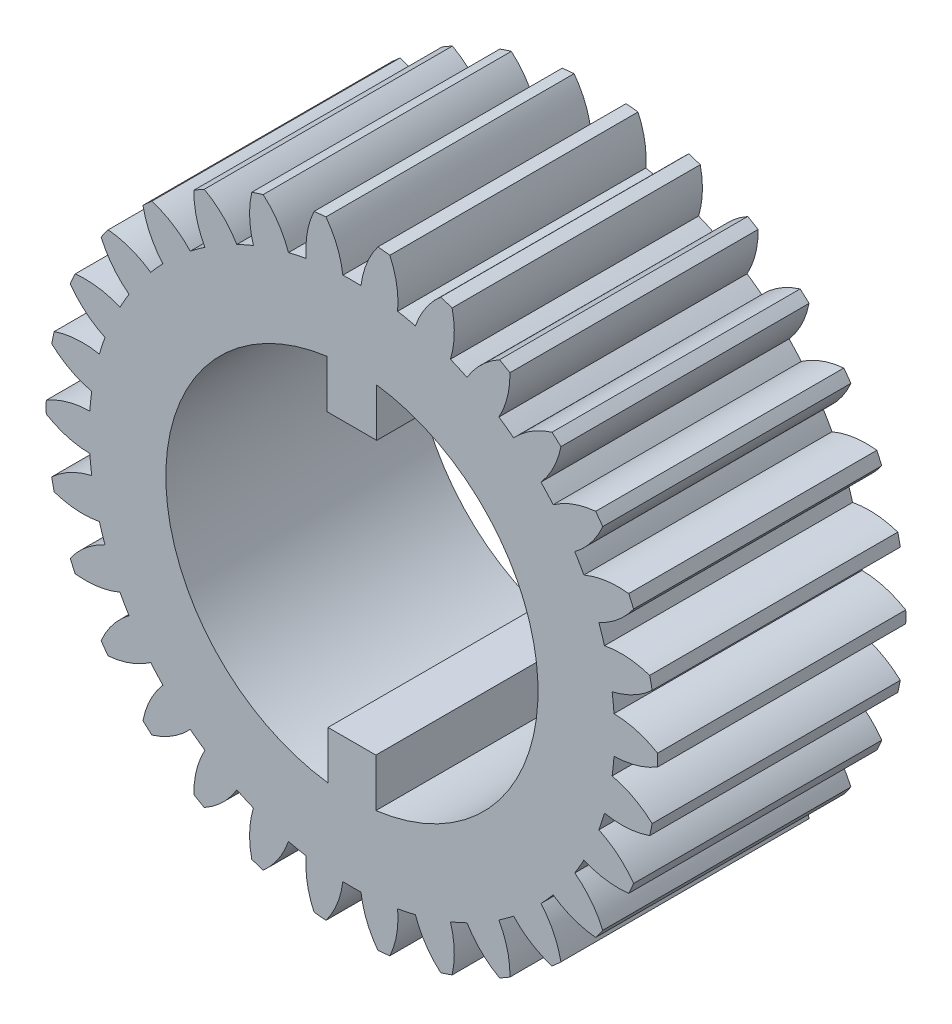
SolidWorks part; units mm, degrees
ref_plane "Front" through (0, 0, 0) normal (0, 0, 1) x (1, 0, 0)
ref_plane "Top" through (0, 0, 0) normal (0, 1, 0) x (1, 0, 0)
ref_plane "Right" through (0, 0, 0) normal (1, 0, 0) x (0, 0, -1)
sketch "Эскиз1" plane through (0, 0, 0) normal (0, 0, 1) x (1, 0, 0)
  circle A0 centre (0, 0) radius 10.5875 construction
  circle A1 centre (0, 0) radius 11.5 construction
  circle A2 centre (0, 0) radius 12.32
  circle A3 centre (0, 0) radius 10.805 construction
  dimension "D1" = 21.175
  dimension "D2" = 23
  dimension "D3" = 24.64
  dimension "D4" = 21.61
extrude "Бобышка-Вытянуть1" add sketch "Эскиз1" along normal mid plane 10
sketch "Эскиз2" plane through (0, 0, 5) normal (0, 0, 1) x (1, 0, 0)
  line L0 (-0.9448, 15.1928) -> (0, 0) construction
  line L1 (-0.7321, 11.7723) -> (-4.9391, 9.6101) construction
  line L2 (-0.6, 11.4843) -> (0.6, 11.4843) construction
  line L3 (0, 0) -> (0, 12.32) construction
  circle A0 centre (0, 0) radius 12.32 construction
  circle A1 centre (0, 0) radius 10.805 construction
  arc A2 (-1.4587, 12.7367) -> (-0.3658, 10.5812) centre (-3.8896, 10.1495) cw
  circle A3 centre (0, 0) radius 10.5875 construction
  circle A4 centre (0, 0) radius 11.5 construction
  arc A5 (1.4587, 12.7367) -> (0.3658, 10.5812) centre (3.8896, 10.1495) ccw
  arc A6 (-0.3658, 10.5812) -> (0.3658, 10.5812) centre (0, 0) cw
  circle A8 centre (0, 0) radius 12.82
  arc A9 (1.4587, 12.7367) -> (-1.4587, 12.7367) centre (0, 0) ccw
  point P3 (-0.7321, 11.7723)
  dimension "D1" = 0.525
  dimension "D2" = 1.2
  dimension "D3" = 4.7301
  dimension "D4" = 1.18
  dimension "D5" = 0.5
sketch "Эскиз4" plane through (0, 0, 0) normal (0, 1, 0) x (1, 0, 0)
  line L0 (0, 5) -> (0, -5)
  line L1 (12.32, 5) -> (-12.32, 5) construction
  line L3 (-12.32, -5) -> (12.32, -5) construction
  line L4 (0, -50) -> (0, 50) construction
  dimension "D1" = 0
curve "Кривая1"
sketch "Эскиз5" plane through (0, 0, -5) normal (0, 0, 1) x (1, 0, 0)
  line L0 (-0.9448, 15.1928) -> (0, 0) construction
  line L1 (-0.7321, 11.7723) -> (-4.9391, 9.6101) construction
  line L2 (-0.6, 11.4843) -> (0.6, 11.4843) construction
  line L3 (0, 0) -> (0, 12.32) construction
  arc A2 (-1.4587, 12.7367) -> (-0.3658, 10.5812) centre (-3.8896, 10.1495) cw
  arc A5 (1.4587, 12.7367) -> (0.3658, 10.5812) centre (3.8896, 10.1495) ccw
  arc A6 (-0.3658, 10.5812) -> (0.3658, 10.5812) centre (0, 0) cw
  arc A9 (1.4587, 12.7367) -> (-1.4587, 12.7367) centre (0, 0) ccw
  point P3 (-0.7321, 11.7723)
loft "Вырез-По сечениям1" cut profiles "Эскиз5", "Эскиз2"
pattern_circular "Круговой массив1" count 30 over 360 about axis through (0, 0, 0) along (0, 0, 1) of "Вырез-По сечениям1"
sketch "Эскиз6" plane through (0, 0, 5) normal (0, 0, 1) x (1, 0, 0)
  line L0 (0, 7.5) -> (0, -7.5) construction
  line L1 (-1, 7.5) -> (1, 7.5)
  line L2 (-1, 7.5) -> (-1, 5.5)
  line L3 (-1, 5.5) -> (1, 5.5)
  line L4 (1, 7.5) -> (1, 5.5)
  line L5 (-0.9649, -7.5) -> (0.9649, -7.5)
  line L6 (-0.9649, -7.5) -> (-0.9649, -5.5)
  line L7 (-0.9649, -5.5) -> (0.9649, -5.5)
  line L8 (0.9649, -7.5) -> (0.9649, -5.5)
  line L9 (-7.5, 0) -> (7.5, 0) construction
  circle A0 centre (0, 0) radius 7.5
  dimension "D1" = 15
  dimension "D2" = 2
  dimension "D3" = 2
extrude "Вырез-Вытянуть1" cut sketch "Эскиз6" against normal blind 10 contours L2 A0 L6 L7 L8 L4 L3
